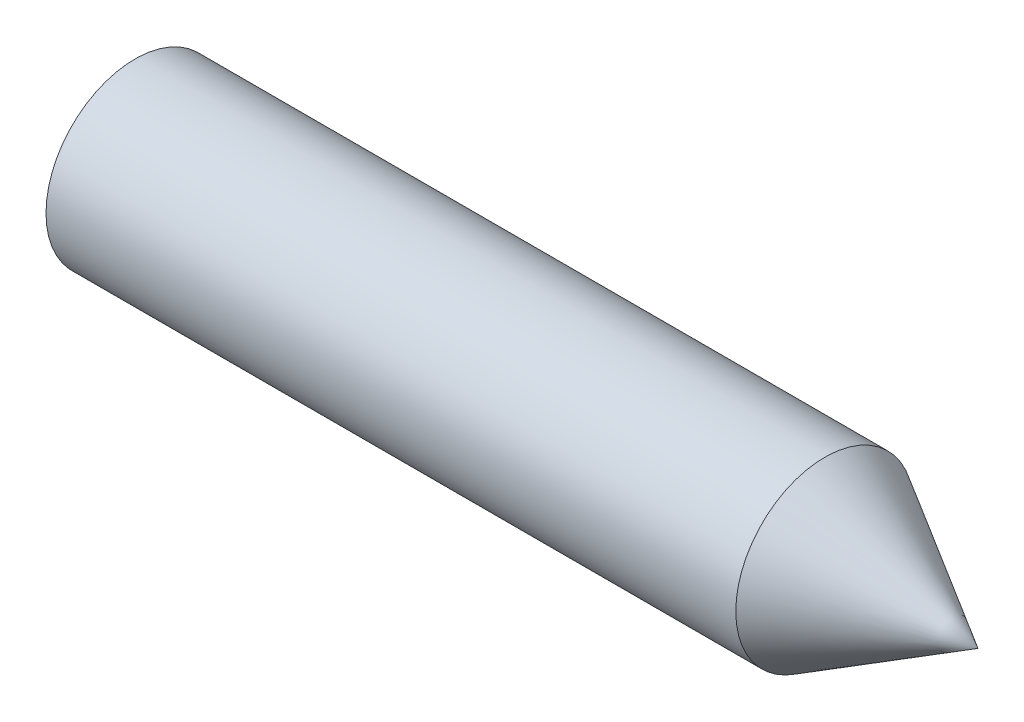
SolidWorks part; units mm, degrees
ref_plane "Front Plane" through (0, 0, 0) normal (0, 0, 1) x (1, 0, 0)
ref_plane "Top Plane" through (0, 0, 0) normal (0, 1, 0) x (1, 0, 0)
ref_plane "Right Plane" through (0, 0, 0) normal (1, 0, 0) x (0, 0, -1)
sketch "Sketch1" plane through (0, 0, 0) normal (0, 0, 1) x (1, 0, 0)
  line L0 (0, 0) -> (25.5663, 0) construction
  line L1 (25.5663, 0) -> (31.242, 0) construction
  line L2 (31.242, 0) -> (25.5663, 3.302)
  line L3 (25.5663, 3.302) -> (0, 3.302)
  line L4 (0, 3.302) -> (0, 0)
  line L5 (25.5663, 3.302) -> (25.5663, 0) construction
  line L6 (0, 0) -> (31.242, 0)
  dimension "D1" = 31.242
  dimension "D2" = 30.19
  dimension "D3" = 3.302
revolve "Revolve1" add sketch "Sketch1" angle 360 about L6
